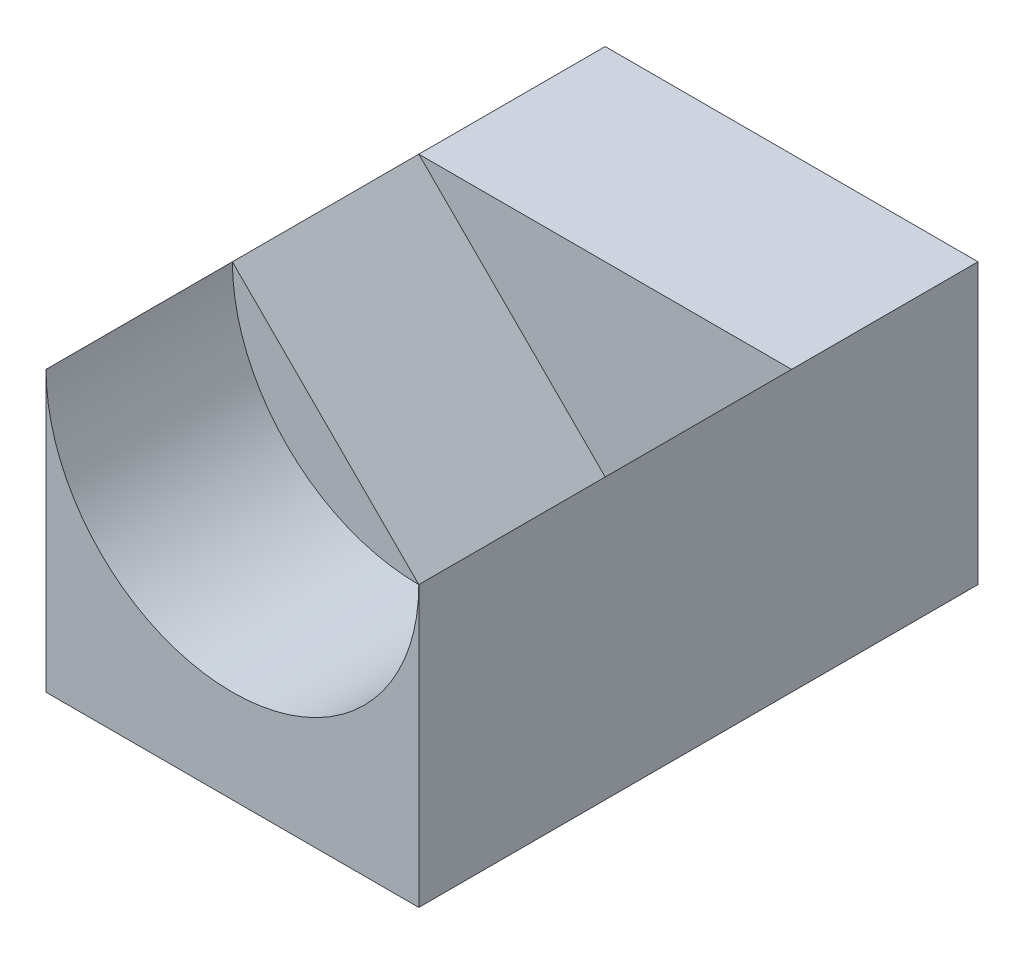
SolidWorks part; units mm, degrees
ref_plane "前基準面" through (0, 0, 0) normal (0, 0, 1) x (1, 0, 0)
ref_plane "上基準面" through (0, 0, 0) normal (0, 1, 0) x (1, 0, 0)
ref_plane "右基準面" through (0, 0, 0) normal (1, 0, 0) x (0, 0, -1)
sketch "草圖1" plane through (0, 0, 0) normal (0, 1, 0) x (1, 0, 0)
  line L1 (-10, 15) -> (10, 15)
  line L2 (-10, 15) -> (-10, -15)
  line L3 (-10, -15) -> (10, -15)
  line L4 (10, 15) -> (10, -15)
  line L5 (-10, 15) -> (10, -15) construction
  line L6 (-10, -15) -> (10, 15) construction
  point P0 (0, 0)
  dimension "D1" = 30
  dimension "D2" = 20
extrude "填料-伸長1" add sketch "草圖1" against normal blind 15
sketch "草圖2" plane through (0, 0, 15) normal (0, 0, 1) x (1, 0, 0)
  line L0 (-10, 0) -> (10, 0) construction
  circle A0 centre (0, 0) radius 10
  dimension "D1" = 20
extrude "除料-伸長1" cut sketch "草圖2" against normal blind 10
sketch "草圖3" plane through (0, 0, 5) normal (0, 0, 1) x (1, 0, 0)
  line L0 (-10, 0) -> (0, -10)
  line L1 (0, -10) -> (10, 0)
  line L2 (10, 0) -> (-10, 0)
  arc A0 (-10, 0) -> (10, 0) centre (0, 0) ccw construction
extrude "除料-伸長2" cut sketch "草圖3" against normal blind 10
